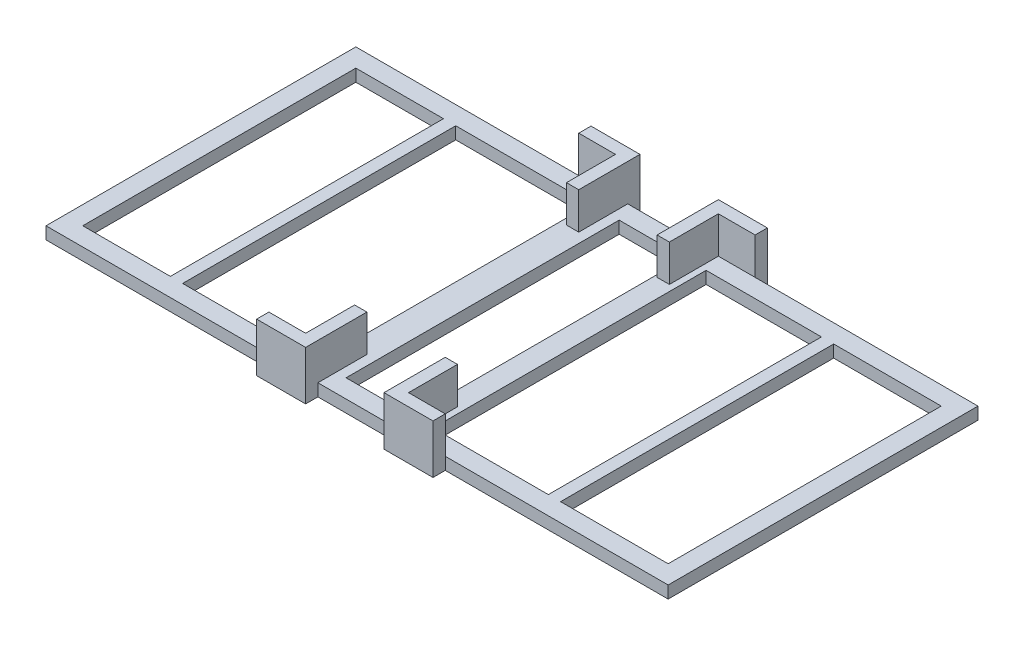
SolidWorks part; units mm, degrees
ref_plane "Front" through (0, 0, 0) normal (0, 0, 1) x (1, 0, 0)
ref_plane "Top" through (0, 0, 0) normal (0, 1, 0) x (1, 0, 0)
ref_plane "Right" through (0, 0, 0) normal (1, 0, 0) x (0, 0, -1)
sketch "草图1" plane through (0, 0, 0) normal (0, 1, 0) x (1, 0, 0)
  line L1 (0, 0) -> (50.8, 0)
  line L2 (0, 0) -> (0, -25.3)
  line L3 (0, -25.3) -> (50.8, -25.3)
  line L4 (50.8, 0) -> (50.8, -25.3)
  dimension "D1" = 25.3
  dimension "D2" = 50.8
extrude "凸台-拉伸1" add sketch "草图1" along normal blind 1
sketch "草图3" plane through (0, 1, 0) normal (0, 1, 0) x (1, 0, 0)
  line L0 (0, -25.3) -> (50.8, -25.3) construction
  line L1 (21.2, -25.3) -> (22.2, -25.3)
  line L2 (21.2, -25.3) -> (21.2, -21.3)
  line L3 (21.2, -21.3) -> (22.2, -21.3)
  line L4 (22.2, -25.3) -> (22.2, -21.3)
  line L5 (50.8, 0) -> (0, 0) construction
  line L6 (21.2, 0) -> (22.2, 0)
  line L7 (21.2, 0) -> (21.2, -4)
  line L8 (21.2, -4) -> (22.2, -4)
  line L9 (22.2, 0) -> (22.2, -4)
  line L10 (50.8, -25.3) -> (50.8, 0) construction
  line L11 (28.6, 0) -> (29.6, 0)
  line L12 (28.6, 0) -> (28.6, -4)
  line L13 (28.6, -4) -> (29.6, -4)
  line L14 (29.6, 0) -> (29.6, -4)
  line L15 (28.6, -25.3) -> (29.6, -25.3)
  line L16 (28.6, -25.3) -> (28.6, -21.3)
  line L17 (28.6, -21.3) -> (29.6, -21.3)
  line L18 (29.6, -25.3) -> (29.6, -21.3)
  dimension "D1" = 1
  dimension "D2" = 1
  dimension "D3" = 1
  dimension "D4" = 1
  dimension "D5" = 4
  dimension "D6" = 4
  dimension "D7" = 4
  dimension "D8" = 4
  dimension "D9" = 21.2
  dimension "D10" = 21.2
  dimension "D11" = 21.2
  dimension "D12" = 21.2
extrude "凸台-拉伸3" add sketch "草图3" along normal blind 3
sketch "草图4" plane through (0, 0, 25.3) normal (0, 0, 1) x (1, 0, 0)
  line L1 (0, 0) -> (50.8, 0) construction
  line L2 (22.2, 4) -> (18.2, 4)
  line L3 (22.2, 4) -> (22.2, 0)
  line L4 (22.2, 0) -> (18.2, 0)
  line L5 (18.2, 4) -> (18.2, 0)
  line L6 (28.6, 4) -> (29.6, 4) construction
  line L7 (28.6, 4) -> (32.6, 4)
  line L8 (28.6, 4) -> (28.6, 0)
  line L9 (28.6, 0) -> (32.6, 0)
  line L10 (32.6, 4) -> (32.6, 0)
  line L11 (28.6, 4) -> (28.6, 1) construction
  dimension "D1" = 4
  dimension "D2" = 4
extrude "凸台-拉伸5" add sketch "草图4" along normal blind 1
sketch "草图5" plane through (0, 0, 0) normal (0, 0, -1) x (-1, 0, 0)
  line L0 (-50.8, 0) -> (0, 0) construction
  line L1 (-22.2, 4) -> (-18.2, 4)
  line L2 (-22.2, 4) -> (-22.2, 0)
  line L3 (-22.2, 0) -> (-18.2, 0)
  line L4 (-18.2, 4) -> (-18.2, 0)
  line L6 (-28.6, 4) -> (-32.6, 4)
  line L7 (-28.6, 4) -> (-28.6, 0)
  line L8 (-28.6, 0) -> (-32.6, 0)
  line L9 (-32.6, 4) -> (-32.6, 0)
  dimension "D1" = 4
  dimension "D2" = 4
extrude "凸台-拉伸6" add sketch "草图5" along normal blind 1
sketch "草图6" plane through (0, 0, 0) normal (0, -1, 0) x (1, 0, 0)
  line L40 (20.7, 1.5) -> (19.7, 1.5)
  line L41 (20.7, 23.8) -> (19.7, 23.8)
  line L42 (30.1, 23.8) -> (31.1, 23.8)
  line L43 (31.1, 1.5) -> (30.1, 1.5)
  line L44 (40.5169, 1.5) -> (49.3, 1.5)
  line L45 (9.6556, 1.5) -> (19.7, 1.5)
  line L46 (8.6556, 1.5) -> (8.6556, 23.8)
  line L47 (8.6556, 23.8) -> (1.5, 23.8)
  line L48 (9.6556, 1.5) -> (9.6556, 23.8)
  line L49 (39.5169, 23.8) -> (31.1, 23.8)
  line L50 (39.5169, 1.5) -> (39.5169, 23.8)
  line L52 (40.5169, 1.5) -> (40.5169, 23.8)
  line L54 (23, 1.5) -> (23, 23.8)
  line L56 (20.7, 1.5) -> (20.7, 23.8)
  line L58 (28.4, 1.5) -> (28.4, 23.8)
  line L60 (1.5, 23.8) -> (1.5, 1.5)
  line L61 (1.5, 1.5) -> (19.7, 1.5)
  line L62 (19.7, 1.5) -> (19.7, 0.5)
  line L63 (19.7, 0.5) -> (20.7, 0.5)
  line L64 (20.7, 0.5) -> (20.7, 1.5)
  line L65 (20.7, 1.5) -> (30.1, 1.5)
  line L66 (30.1, 1.5) -> (30.1, 0.5)
  line L67 (30.1, 0.5) -> (31.1, 0.5)
  line L68 (31.1, 0.5) -> (31.1, 1.5)
  line L69 (31.1, 1.5) -> (49.3, 1.5)
  line L70 (49.3, 1.5) -> (49.3, 23.8)
  line L71 (49.3, 23.8) -> (31.1, 23.8)
  line L72 (31.1, 23.8) -> (31.1, 24.8)
  line L73 (31.1, 24.8) -> (30.1, 24.8)
  line L74 (30.1, 24.8) -> (30.1, 23.8)
  line L75 (30.1, 23.8) -> (20.7, 23.8)
  line L76 (20.7, 23.8) -> (20.7, 24.8)
  line L77 (20.7, 24.8) -> (19.7, 24.8)
  line L78 (19.7, 24.8) -> (19.7, 23.8)
  line L79 (19.7, 23.8) -> (1.5, 23.8)
  line L80 (1.5, 23.8) -> (1.5, 1.5)
  line L81 (1.5, 1.5) -> (8.6556, 1.5)
  line L82 (30.1, 1.5) -> (30.1, 23.8)
  line L85 (23, 1.5) -> (28.4, 1.5)
  line L89 (31.1, 1.5) -> (39.5169, 1.5)
  line L90 (49.3, 1.5) -> (49.3, 23.8)
  line L91 (49.3, 23.8) -> (40.5169, 23.8)
  line L95 (28.4, 23.8) -> (23, 23.8)
  line L99 (19.7, 23.8) -> (9.6556, 23.8)
  dimension "D2" = 1
  dimension "D3" = 1
  dimension "D1" = 1.5
extrude "切除-拉伸1" cut sketch "草图6" against normal through all
